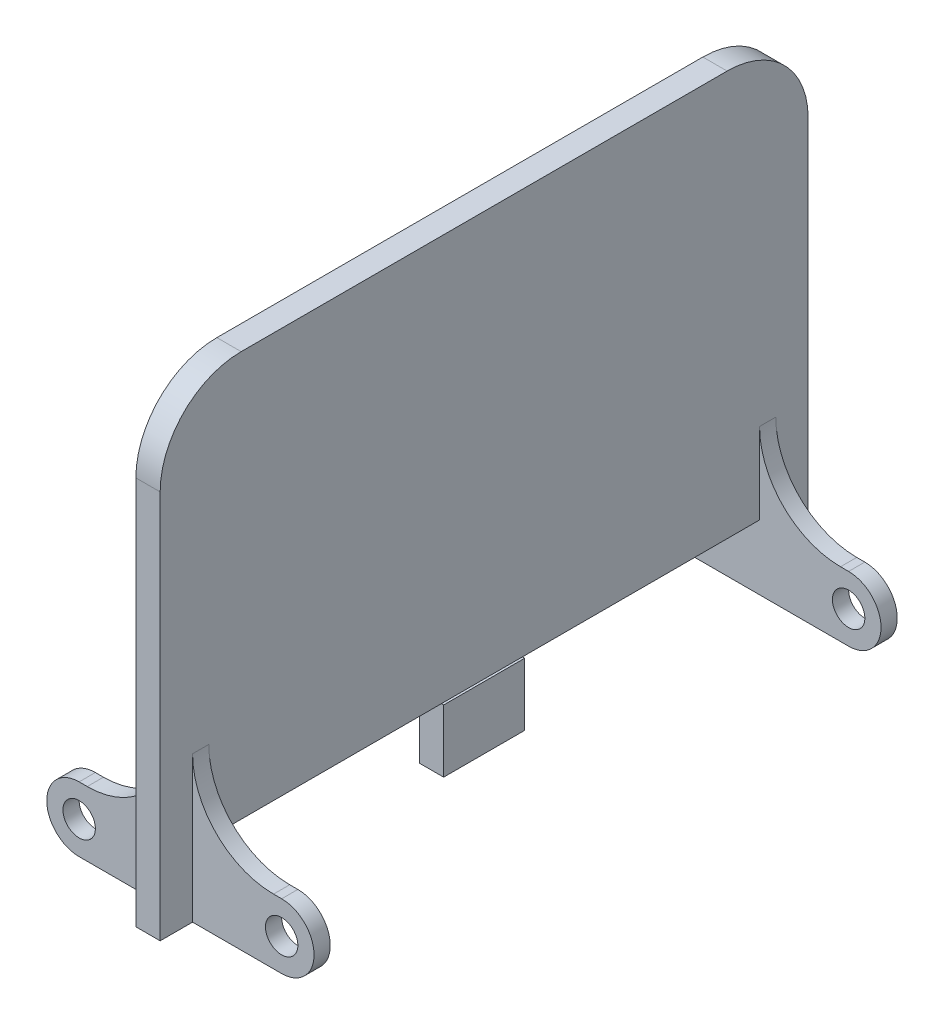
SolidWorks part; units mm, degrees
ref_plane "Front Plane" through (0, 0, 0) normal (0, 0, 1) x (1, 0, 0)
ref_plane "Top Plane" through (0, 0, 0) normal (0, 1, 0) x (1, 0, 0)
ref_plane "Right Plane" through (0, 0, 0) normal (1, 0, 0) x (0, 0, -1)
sketch "Sketch1" plane through (0, 0, 0) normal (0, 0, 1) x (1, 0, 0)
  line L0 (0, 0) -> (25, 0) construction
  line L1 (0, 4) -> (25, 4)
  line L2 (0, -4) -> (25, -4)
  arc A4 (0, 4) -> (0, -4) centre (0, 0) ccw
  arc A5 (25, -4) -> (25, 4) centre (25, 0) ccw
  circle A6 centre (0, 0) radius 2
  circle A7 centre (25, 0) radius 2
  point P2 (12.5, 0)
  dimension "D1" = 4
  dimension "D2" = 4
  dimension "D3" = 25
extrude "Boss-Extrude1" add sketch "Sketch1" along normal blind 2
sketch "Sketch2" plane through (0, 4, 0) normal (0, 1, 0) x (1, 0, 0)
  line L1 (11, 4) -> (14, 4)
  line L2 (11, 4) -> (11, -36)
  line L3 (11, -36) -> (14, -36)
  line L4 (14, 4) -> (14, -36)
  line L6 (25, 0) -> (0, 0) construction
  line L7 (25, -2) -> (0, -2) construction
  point P7 (12.5, 0)
  point P8 (12.5, 4)
  dimension "D1" = 3
  dimension "D2" = 34
  dimension "D3" = 40
extrude "Boss-Extrude2" add sketch "Sketch2" along normal blind 50
sketch "Sketch4" plane through (0, 4, 0) normal (0, -1, 0) x (1, 0, 0)
  line L1 (11, 0) -> (14, 0)
  line L2 (11, 0) -> (11, -4)
  line L3 (11, -4) -> (14, -4)
  line L4 (14, 0) -> (14, -4)
extrude "Boss-Extrude4" add sketch "Sketch4" along normal up to surface (8 mm away) up to face at (12.5, -4, 1)
ref_plane "Plane1" through (0, 0, 36) normal (0, 0, 1) x (1, 0, 0)
fillet "Fillet1" radius 10 2 edges at (11, 4, 1) (14, 4, 1)
mirror "Mirror1" about plane through (0, 0, 36) normal (0, 0, 1) of "Boss-Extrude2"
mirror "Mirror2" about plane through (0, 0, 36) normal (0, 0, 1) of "Boss-Extrude4", "Boss-Extrude1", "Fillet1"
fillet "Fillet2" radius 10 2 edges at (12.5, 54, -4) (12.5, 54, 76)
sketch "Sketch3" plane through (14, 0, 0) normal (1, 0, 0) x (0, 0, -1)
  line L0 (-36, 55) -> (-36, -55) construction
  line L1 (-41, 3.72) -> (-31, 3.72)
  line L2 (-41, 3.72) -> (-41, -4)
  line L3 (-41, -4) -> (-31, -4)
  line L4 (-31, 3.72) -> (-31, -4)
  line L5 (-70, 4) -> (-2, 4) construction
  line L7 (-72, -4) -> (-76, -4) construction
  point P4 (-36, 3.72)
  dimension "D1" = 10
  dimension "D2" = 0.28
extrude "Boss-Extrude3" add sketch "Sketch3" against normal up to surface (3 mm away) separate body up to face at (11, 17.7244, 36)
equation "\"link_thickness\"= 2mm"
equation "\"bolt_length\"= 80mm"
equation "\"nut_length\"= 4mm"
equation "\"inner_spacing\"= \"bolt_length\" - \"nut_length\" - \"link_thickness\" * 4"
equation "\"D1@Boss-Extrude1\"=\"link_thickness\""
equation "\"D2@Sketch2\"= \"inner_spacing\"/2"
